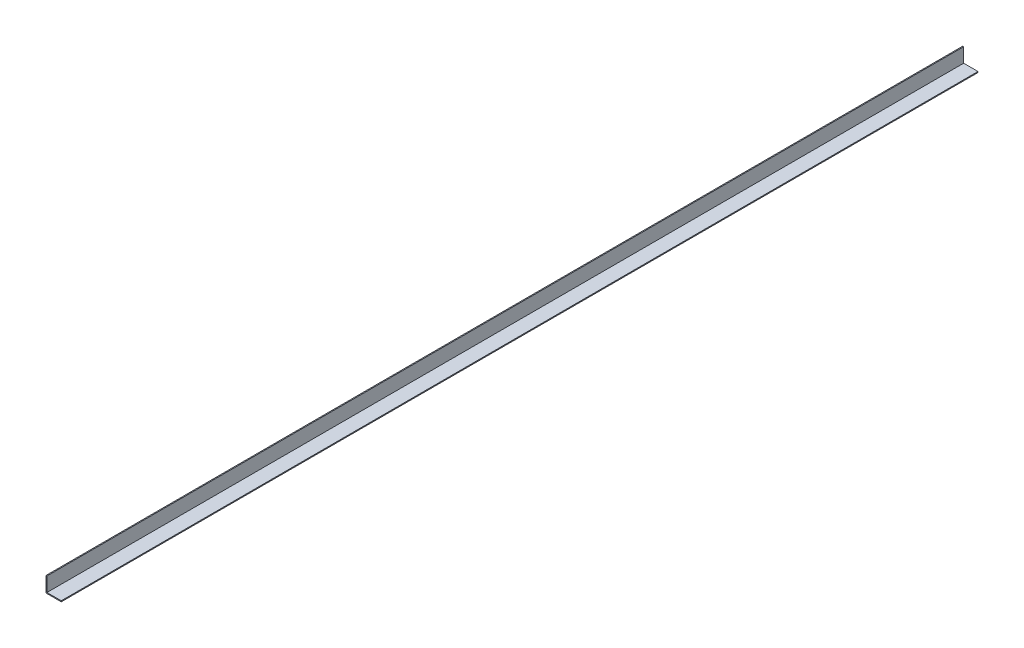
SolidWorks part; units mm, degrees
material "ASTM A36 Acero"
ref_plane "Alzado" through (0, 0, 0) normal (0, 0, 1) x (1, 0, 0)
ref_plane "Planta" through (0, 0, 0) normal (0, 1, 0) x (1, 0, 0)
ref_plane "Vista lateral" through (0, 0, 0) normal (1, 0, 0) x (0, 0, -1)
sketch "Croquis1" plane through (0, 0, 0) normal (0, 0, 1) x (1, 0, 0)
  line L0 (0, 101.6) -> (0, 0)
  line L1 (0, 0) -> (101.6, 0)
  line L2 (101.6, 0) -> (101.6, 6.35)
  line L3 (101.6, 6.35) -> (6.35, 6.35)
  line L4 (6.35, 6.35) -> (6.35, 101.6)
  line L5 (6.35, 101.6) -> (0, 101.6)
  dimension "D1" = 6.35
  dimension "D2" = 101.6
extrude "Saliente-Extruir1" add sketch "Croquis1" against normal blind 6100
